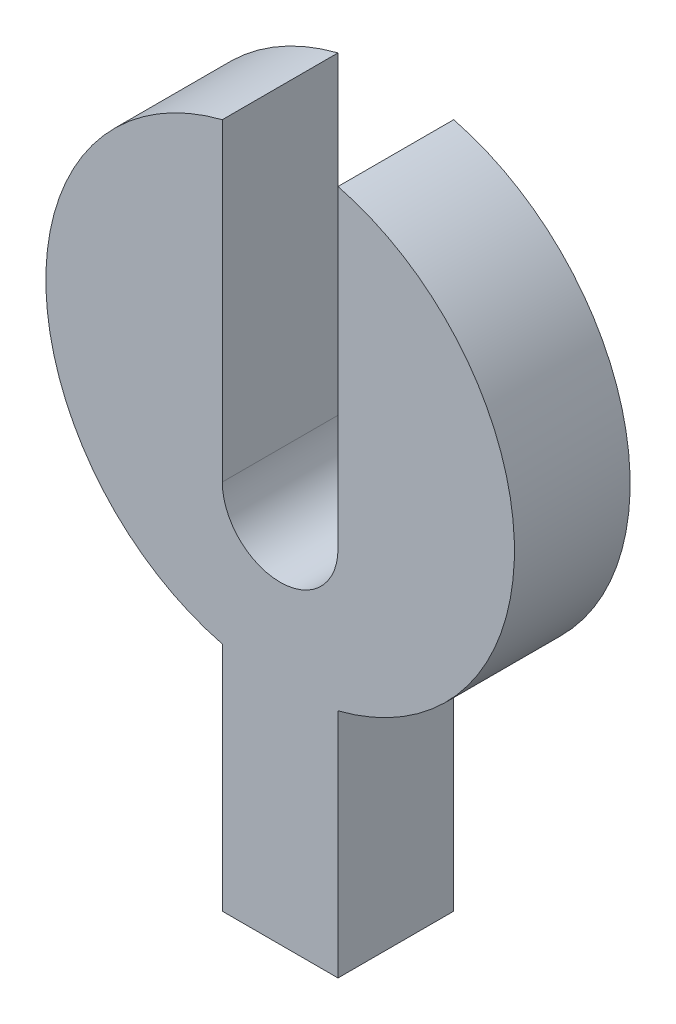
SolidWorks part; units mm, degrees
ref_plane "Plan de face" through (0, 0, 0) normal (0, 0, 1) x (1, 0, 0)
ref_plane "Plan de dessus" through (0, 0, 0) normal (0, 1, 0) x (1, 0, 0)
ref_plane "Plan de droite" through (0, 0, 0) normal (1, 0, 0) x (0, 0, -1)
sketch "Esquisse1" plane through (0, 0, 0) normal (0, 0, 1) x (1, 0, 0)
  line L0 (-2, 7.8492) -> (-2, -3)
  line L1 (2, 7.8492) -> (2, -3)
  line L2 (-2, 7.8492) -> (2, 7.8492) construction
  line L3 (-2, -7.8492) -> (2, -15.8492) construction
  line L4 (-2, -7.8492) -> (2, -7.8492)
  line L5 (-2, -7.8492) -> (-2, -15.8492)
  line L6 (-2, -15.8492) -> (2, -15.8492)
  line L7 (2, -7.8492) -> (2, -15.8492)
  arc A1 (2, 7.8492) -> (-2, 7.8492) centre (0, 0) cw
  arc A3 (-2, -3) -> (2, -3) centre (0, -3) ccw
  point P9 (0, 7.8492)
  point P11 (0, -11.8492)
  dimension "D1" = 8.1
  dimension "D2" = 4
  dimension "D3" = 3
  dimension "D4" = 8
extrude "Boss.-Extru.1" add sketch "Esquisse1" along normal blind 4
